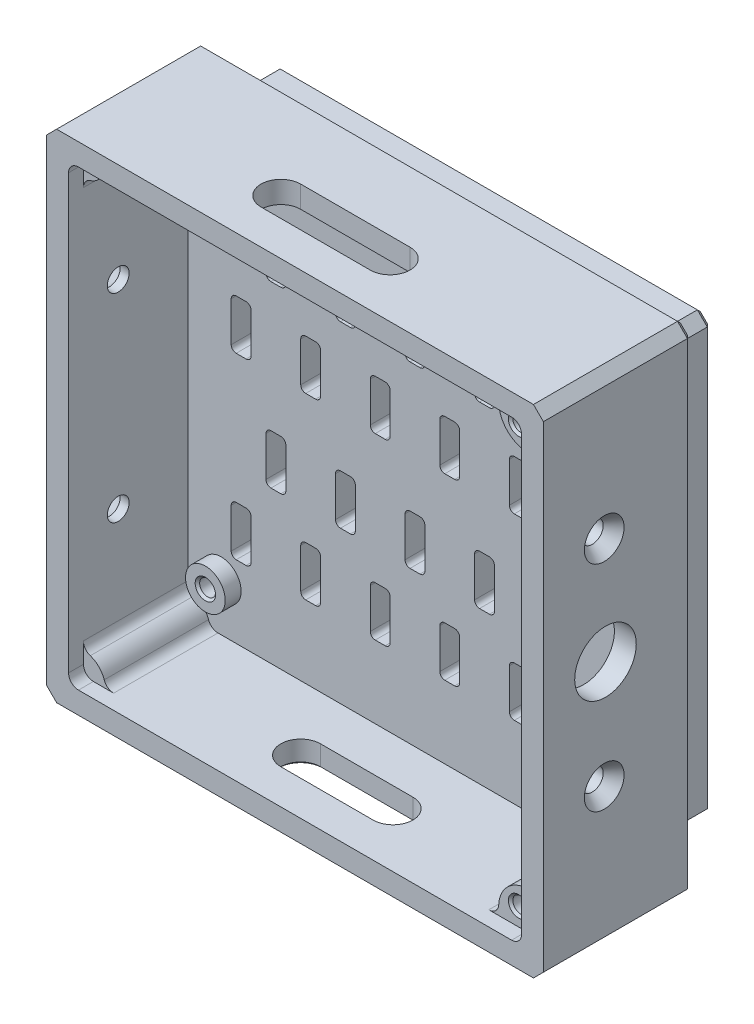
SolidWorks part; units mm, degrees
ref_plane "前视基准面" through (0, 0, 0) normal (0, 0, 1) x (1, 0, 0)
ref_plane "上视基准面" through (0, 0, 0) normal (0, 1, 0) x (1, 0, 0)
ref_plane "右视基准面" through (0, 0, 0) normal (1, 0, 0) x (0, 0, -1)
sketch "草图1" plane through (0, 0, 0) normal (0, 0, 1) x (1, 0, 0)
  line L1 (-25, 25) -> (25, 25)
  line L2 (-25, 25) -> (-25, -25)
  line L3 (-25, -25) -> (25, -25)
  line L4 (25, 25) -> (25, -25)
  line L5 (-25, 25) -> (25, -25) construction
  line L6 (-25, -25) -> (25, 25) construction
  point P0 (0, 0)
  dimension "D1" = 50
  dimension "D2" = 50
extrude "凸台-拉伸1" add sketch "草图1" along normal blind 20
sketch "草图2" plane through (0, 0, 20) normal (0, 0, 1) x (1, 0, 0)
  line L0 (25, -25) -> (25, 25) construction
  line L1 (-22.8, 22.8) -> (22.8, 22.8)
  line L2 (-22.8, 22.8) -> (-22.8, -22.8)
  line L3 (-22.8, -22.8) -> (22.8, -22.8)
  line L4 (22.8, 22.8) -> (22.8, -22.8)
  line L5 (-22.8, 22.8) -> (22.8, -22.8) construction
  line L6 (-22.8, -22.8) -> (22.8, 22.8) construction
  line L7 (-25, -25) -> (25, -25) construction
  point P0 (0, 0)
  dimension "D1" = 2.2
  dimension "D2" = 2.2
extrude "切除-拉伸1" cut sketch "草图2" against normal blind 12
sketch "草图3" plane through (0, 0, 8) normal (0, 0, 1) x (1, 0, 0)
  circle A0 centre (-19.427, 18) radius 2
  circle A1 centre (16.5731, 18) radius 2
  circle A2 centre (16.5731, -18) radius 2
  circle A3 centre (-19.427, -18) radius 2
  dimension "D1" = 4
  dimension "D2" = 4
  dimension "D3" = 4
  dimension "D4" = 4
extrude "凸台-拉伸2" add sketch "草图3" along normal blind 1.6
hole_wizard "M2 螺纹孔1" positions "草图6" profile "草图7" tap size "M2" standard "GB"
sketch "草图6" plane through (0, 0, 9.6) normal (0, 0, 1) x (1, 0, 0)
  point P0 (-19.427, 18)
  point P3 (16.5731, 18)
  point P6 (16.5731, -18)
  point P9 (-19.427, -18)
sketch "草图7" plane through (-19.427, 18, 9.6) normal (1, 0, 0) x (0, -1, 0)
  line L0 (0, 0) -> (0, 6.4807)
  line L1 (0, 6.4807) -> (0.8, 6)
  line L2 (0.8, 6) -> (0.8, 0.225)
  line L3 (0.8, 0.225) -> (1.025, 0)
  line L5 (1.025, 0) -> (0, 0)
  line L6 (-0.8, 0.225) -> (-1.025, 0) construction
  line L10 (0, 6.4807) -> (-0.8, 6) construction
  line L11 (0, -6.35) -> (0, 107.95) construction
  dimension "螺纹孔钻头直径" = 1.6
  dimension "螺纹孔钻头深度" = 6
  dimension "近端锥形沉头孔直径" = 2.05
  dimension "近端锥形沉头孔角度" = 90
  dimension "导头角度" = 118
cosmetic thread "孔螺蚊线5" parameters "D1"=4, "D2"=2
cosmetic thread "孔螺蚊线6" parameters "D1"=4, "D2"=2
cosmetic thread "孔螺蚊线7" parameters "D1"=4, "D2"=2
cosmetic thread "孔螺蚊线8" parameters "D1"=4, "D2"=2
sketch "草图8" plane through (0, 0, 8) normal (0, 0, 1) x (1, 0, 0)
  line L3 (-22.8, 22.8) -> (-22.8, -22.8) construction
  line L11 (22.8, 22.8) -> (-22.8, 22.8) construction
  line L12 (25, 25) -> (-25, 25) construction
  line L14 (25, -25) -> (25, 25) construction
  line L15 (-25, -25) -> (25, -25) construction
  circle A5 centre (-22.8, 22.8) radius 2.2
  circle A6 centre (22, 22) radius 3
  circle A7 centre (-22.8, -22.8) radius 2.2
  circle A8 centre (22, -22) radius 3
  dimension "D1" = 6
  dimension "D2" = 6
extrude "凸台-拉伸7" add sketch "草图8" along normal offset from surface (10.5 mm away) 1.5 up to face at (0, 0, 20)
fillet "圆角1" radius 1 12 edges at (22.8, -22.8, 19.25) (-22.8, -22.8, 19.25) (-22.8, 22.8, 19.25) (22.8, 22.8, 19.25) (22.8, 19.1086, 13.25) (19.1086, 22.8, 13.25) (22.8, -19.1086, 13.25) (19.1086, -22.8, 13.25) (-20.6, -22.8, 13.25) (-22.8, -20.6, 13.25) (-20.6, 22.8, 13.25) (-22.8, 20.6, 13.25)
hole_wizard "M2 螺纹孔4" positions "草图14" profile "草图15" tap size "M2" standard "GB"
sketch "草图14" plane through (0, 0, 18.5) normal (0, 0, 1) x (1, 0, 0)
  line L0 (22.8, -21.8) -> (22.8, 21.8) construction
  line L1 (21.8, 22.8) -> (-21.8, 22.8) construction
  line L3 (-21.8, -22.8) -> (21.8, -22.8) construction
  point P0 (21, 21)
  point P2 (21, -21)
  dimension "D1" = 1.8
  dimension "D2" = 1.8
  dimension "D3" = 1.8
sketch "草图15" plane through (21, 21, 18.5) normal (1, 0, 0) x (0, -1, 0)
  line L0 (0, 0) -> (0, 6.4807)
  line L1 (0, 6.4807) -> (0.8, 6)
  line L2 (0.8, 6) -> (0.8, 0.225)
  line L3 (0.8, 0.225) -> (1.025, 0)
  line L5 (1.025, 0) -> (0, 0)
  line L6 (-0.8, 0.225) -> (-1.025, 0) construction
  line L10 (0, 6.4807) -> (-0.8, 6) construction
  line L11 (0, -6.35) -> (0, 107.95) construction
  dimension "螺纹孔钻头直径" = 1.6
  dimension "螺纹孔钻头深度" = 6
  dimension "近端锥形沉头孔直径" = 2.05
  dimension "近端锥形沉头孔角度" = 90
  dimension "导头角度" = 118
cosmetic thread "孔螺蚊线11" parameters "D1"=4, "D2"=2
cosmetic thread "孔螺蚊线12" parameters "D1"=4, "D2"=2
sketch "草图16" plane through (-25, 0, 0) normal (-1, 0, 0) x (0, 0, 1)
  line L0 (15, 10) -> (15, -10) construction
  line L1 (20, 25) -> (20, -25) construction
  circle A0 centre (15, 10) radius 1.1
  circle A1 centre (15, -10) radius 1.1
  point P5 (15, 0)
  dimension "D1" = 2.2
  dimension "D2" = 2.2
  dimension "D3" = 20
  dimension "D4" = 5
extrude "切除-拉伸2" cut sketch "草图16" against normal blind 11.5
chamfer "倒角1" distance 0.9 distance2 1.3 2 edges at (-25, 8.9, 15) (-25, -11.1, 15)
sketch "草图17" plane through (0, 25, 0) normal (0, 1, 0) x (1, 0, 0)
  line L0 (-6.927, -12.5) -> (4.073, -12.5) construction
  line L1 (4.073, -16.5) -> (-6.927, -16.5) construction
  line L2 (-6.927, -12.5) -> (4.073, -12.5)
  line L3 (4.073, -16.5) -> (-6.927, -16.5)
  arc A0 (-6.927, -12.5) -> (-6.927, -16.5) centre (-6.927, -14.5) ccw construction
  arc A1 (4.073, -16.5) -> (4.073, -12.5) centre (4.073, -14.5) ccw construction
  arc A2 (-6.927, -12.5) -> (-6.927, -16.5) centre (-6.927, -14.5) ccw
  arc A3 (4.073, -16.5) -> (4.073, -12.5) centre (4.073, -14.5) ccw
extrude "切除-拉伸3" cut sketch "草图17" against normal blind 3
sketch "草图18" plane through (0, 0, 0) normal (0, 0, -1) x (-1, 0, 0)
  line L0 (-22, 22) -> (-22, -22)
  line L1 (-22, -22) -> (22, -22)
  line L2 (22, -22) -> (22, 22)
  line L3 (22, 22) -> (-22, 22)
  line L4 (-25, 25) -> (-25, -25)
  line L5 (-25, -25) -> (25, -25)
  line L6 (25, -25) -> (25, 25)
  line L7 (25, 25) -> (-25, 25)
  line L8 (-25, 25) -> (-25, -25)
  line L9 (-25, -25) -> (25, -25)
  line L10 (25, -25) -> (25, 25)
  line L11 (25, 25) -> (-25, 25)
  dimension "D1" = 0
  dimension "D2" = 3
extrude "切除-拉伸4" cut sketch "草图18" against normal blind 5
chamfer "倒角2" distance 1 angle 45 8 edges at (-22, -22, 2.5) (22, -22, 2.5) (22, 22, 2.5) (-22, 22, 2.5) (-25, 25, 12.5) (-25, -25, 12.5) (25, -25, 12.5) (25, 25, 12.5)
sketch "草图19" plane through (0, 0, 0) normal (0, 0, -1) x (-1, 0, 0)
  line L0 (-11.5731, 10.5) -> (-11.5731, 15.5) construction
  line L1 (-15.0731, 15.5) -> (-13.0731, 15.5)
  line L2 (-15.0731, 15.5) -> (-15.0731, 10.5)
  line L3 (-15.0731, 10.5) -> (-13.0731, 10.5)
  line L4 (-13.0731, 15.5) -> (-13.0731, 10.5)
  line L6 (-14.4731, 12.4) -> (-13.6731, 12.4) construction
  line L7 (-13.6731, -4.4) -> (-14.4731, -4.4) construction
  line L8 (-15.0731, -2.5) -> (-13.0731, -2.5)
  line L9 (-15.0731, -2.5) -> (-15.0731, -7.5)
  line L10 (-15.0731, -7.5) -> (-13.0731, -7.5)
  line L11 (-13.0731, -2.5) -> (-13.0731, -7.5)
  line L12 (-11.5731, -7.5) -> (-11.5731, -2.5) construction
  point P6 (-11.5731, 13)
  point P7 (-13.0731, 13)
  point P10 (-14.0731, 12.4)
  point P11 (-14.0731, 15.5)
  point P18 (-14.0731, -4.4)
  point P19 (-14.0731, -2.5)
  point P22 (-11.5731, -5)
  point P23 (-13.0731, -5)
  dimension "D1" = 5
  dimension "D2" = 2
  dimension "D3" = 5
  dimension "D4" = 2
extrude "切除-拉伸5" cut sketch "草图19" against normal through all
fillet "圆角2" radius 0.5 8 edges at (15.0731, -7.5, 4) (13.0731, -7.5, 4) (13.0731, -2.5, 4) (15.0731, -2.5, 4) (15.0731, 10.5, 4) (13.0731, 10.5, 4) (15.0731, 15.5, 4) (13.0731, 15.5, 4)
pattern_linear "阵列(线性)1" count 5 spacing 7 along (-1, 0, 0) of "切除-拉伸5", "圆角2"
sketch "草图20" plane through (0, 0, 0) normal (0, 0, -1) x (-1, 0, 0)
  line L1 (-11.5731, 7.5) -> (-9.5731, 7.5)
  line L2 (-11.5731, 7.5) -> (-11.5731, 2.5)
  line L3 (-11.5731, 2.5) -> (-9.5731, 2.5)
  line L4 (-9.5731, 7.5) -> (-9.5731, 2.5)
  line L5 (-11.5731, -10.5) -> (-9.5731, -10.5)
  line L6 (-11.5731, -10.5) -> (-11.5731, -15.5)
  line L7 (-11.5731, -15.5) -> (-9.5731, -15.5)
  line L8 (-9.5731, -10.5) -> (-9.5731, -15.5)
  line L9 (-8.0731, 7.5) -> (-13.0731, 7.5) construction
  line L10 (-8.0731, -10.5) -> (-13.0731, -10.5) construction
  line L11 (-13.0731, -10.5) -> (-13.0731, -15.5) construction
  line L12 (-13.0731, 6.3) -> (-13.0731, 3.7) construction
  point P14 (-10.5731, 7.5)
  point P15 (-10.5731, 7.5)
  point P18 (-10.5731, -10.5)
  point P19 (-10.5731, -10.5)
  point P22 (-13.0731, -13)
  point P23 (-11.5731, -13)
  point P26 (-13.0731, 5)
  point P27 (-11.5731, 5)
  dimension "D1" = 2
  dimension "D2" = 5
  dimension "D3" = 2
  dimension "D4" = 5
extrude "切除-拉伸6" cut sketch "草图20" against normal through all
fillet "圆角3" radius 0.5 8 edges at (9.5731, -10.5, 4) (11.5731, -10.5, 4) (9.5731, -15.5, 4) (11.5731, -15.5, 4) (9.5731, 2.5, 4) (11.5731, 2.5, 4) (11.5731, 7.5, 4) (9.5731, 7.5, 4)
pattern_linear "阵列(线性)2" count 5 spacing 7 along (-1, 0, 0) of "切除-拉伸6", "圆角3"
sketch "草图21" plane through (25, 0, 0) normal (1, 0, 0) x (0, 0, -1)
  arc A4 (-13.7499, 3.0459) -> (-13.7499, -3.1539) centre (-13.7499, -0.054) ccw
  arc A5 (-13.7499, -3.1539) -> (-13.7499, 3.0459) centre (-13.7499, -0.054) ccw
  arc A6 (-13.7499, 3.0459) -> (-13.7499, -3.1539) centre (-13.7499, -0.054) ccw
  arc A7 (-13.7499, -3.1539) -> (-13.7499, 3.0459) centre (-13.7499, -0.054) ccw
  dimension "D1" = 0.1
extrude "切除-拉伸8" cut sketch "草图21" against normal blind 3
chamfer "倒角3" distance 0.5 angle 45 16 edges at (-21.5, 21.5, 0) (-22, 0, 0) (-21.5, -21.5, 0) (0, -22, 0) (21.5, -21.5, 0) (0, 22, 0) (21.5, 21.5, 0) (22, 0, 0) (24.5, 24.5, 5) (0, 25, 5) (-24.5, 24.5, 5) (-25, 0, 5) (-24.5, -24.5, 5) (0, -25, 5) (24.5, -24.5, 5) (25, 0, 5)
sketch "草图22" plane through (0, -25, 0) normal (0, -1, 0) x (1, 0, 0)
  line L2 (-4.937, 12.5) -> (4.363, 12.5)
  line L3 (4.363, 16.5) -> (-4.937, 16.5)
  line L4 (-4.937, 12.5) -> (4.363, 12.5)
  line L5 (4.363, 16.5) -> (-4.937, 16.5)
  arc A2 (4.363, 12.5) -> (4.363, 16.5) centre (4.363, 14.5) ccw
  arc A3 (-4.937, 16.5) -> (-4.937, 12.5) centre (-4.937, 14.5) ccw
  arc A4 (4.363, 12.5) -> (4.363, 16.5) centre (4.363, 14.5) ccw
  arc A5 (-4.937, 16.5) -> (-4.937, 12.5) centre (-4.937, 14.5) ccw
  dimension "D1" = 0
extrude "切除-拉伸9" cut sketch "草图22" against normal blind 10
chamfer "倒角4" distance 0.2 angle 45 4 edges at (-0.287, -25, 12.5) (6.363, -25, 14.5) (-6.937, -25, 14.5) (-0.287, -25, 16.5)
sketch "草图23" plane through (22.8, 0, 0) normal (-1, 0, 0) x (0, 0, 1)
  circle A0 centre (13.8769, 10.741) radius 0.8 construction
  circle A1 centre (13.8769, 10.741) radius 0.8 construction
  circle A2 centre (13.8769, -10.849) radius 0.8 construction
  circle A3 centre (13.8769, -10.849) radius 0.8 construction
  circle A4 centre (13.8769, 10.741) radius 1.1
  circle A5 centre (13.8769, -10.849) radius 1.1
  dimension "D1" = 2.2
  dimension "D2" = 2.2
extrude "切除-拉伸10" cut sketch "草图23" against normal blind 10
chamfer "倒角5" distance 1.2 distance2 0.9 2 edges at (25, -11.949, 13.8769) (25, 9.641, 13.8769)
sketch "草图24" plane through (0, 0, 0) normal (0, 0, -1) x (-1, 0, 0)
  line L0 (0, 20) -> (0, -20) construction
  point P2 (0, 0)
  dimension "D1" = 40
  dimension "D2" = 5
